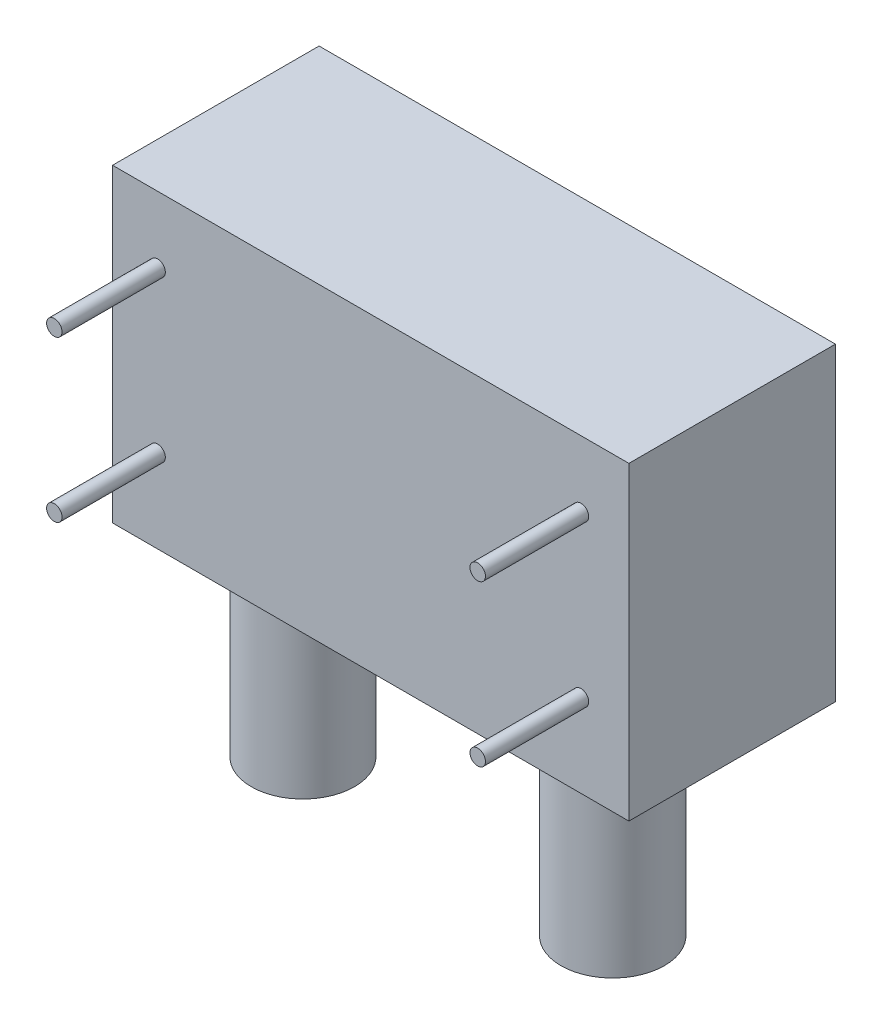
SolidWorks part; units mm, degrees
ref_plane "Front Plane" through (0, 0, 0) normal (0, 0, 1) x (1, 0, 0)
ref_plane "Top Plane" through (0, 0, 0) normal (0, 1, 0) x (1, 0, 0)
ref_plane "Right Plane" through (0, 0, 0) normal (1, 0, 0) x (0, 0, -1)
sketch "Sketch1" plane through (0, 0, 0) normal (0, 0, 1) x (1, 0, 0)
  line L1 (-117.3485, 46.3331) -> (-67.3485, 46.3331)
  line L2 (-117.3485, 46.3331) -> (-117.3485, 16.3331)
  line L3 (-117.3485, 16.3331) -> (-67.3485, 16.3331)
  line L4 (-67.3485, 46.3331) -> (-67.3485, 16.3331)
  line L5 (-117.3485, 46.3331) -> (-67.3485, 16.3331) construction
  line L6 (-117.3485, 16.3331) -> (-67.3485, 46.3331) construction
  point P0 (-92.3485, 31.3331)
  dimension "D1" = 50
  dimension "D2" = 30
  dimension "D3" = 67.3485
  dimension "D4" = 31.3331
extrude "Boss-Extrude1" add sketch "Sketch1" along normal blind 20
sketch "Sketch2" plane through (0, 16.3331, 0) normal (0, -1, 0) x (1, 0, 0)
  line L0 (-67.3485, 20) -> (-67.3485, 0) construction
  line L1 (-117.3485, 0) -> (-67.3485, 0) construction
  circle A0 centre (-108.5128, 10.4041) radius 5
  circle A1 centre (-78.5128, 10.4041) radius 5.0156
  dimension "D1" = 10
  dimension "D2" = 30
  dimension "D3" = 10.0311
  dimension "D4" = 11.1643
  dimension "D5" = 10.4041
extrude "Boss-Extrude3" add sketch "Sketch2" along normal blind 20
sketch "Sketch3" plane through (0, 0, 20) normal (0, 0, 1) x (1, 0, 0)
  line L0 (-114.9657, 42.147) -> (-69.9657, 42.147) construction
  line L1 (-69.9657, 42.147) -> (-69.9657, 22.147) construction
  line L2 (-69.9657, 22.147) -> (-114.9657, 22.147) construction
  line L3 (-114.9657, 22.147) -> (-114.9657, 42.147) construction
  line L4 (-114.9657, 32.147) -> (-69.9657, 32.147) construction
  line L5 (-67.3485, 16.3331) -> (-67.3485, 46.3331) construction
  line L6 (-67.3485, 46.3331) -> (-117.3485, 46.3331) construction
  circle A0 centre (-112.9881, 39.9081) radius 0.75
  circle A1 centre (-71.9881, 39.9155) radius 0.75
  circle A2 centre (-71.9881, 24.3785) radius 0.75
  circle A3 centre (-112.9881, 24.3859) radius 0.75
  dimension "D3" = 41
  dimension "D4" = 1.5
  dimension "D5" = 1.5
  dimension "D1" = 45
  dimension "D2" = 20
extrude "Boss-Extrude4" add sketch "Sketch3" along normal blind 10
